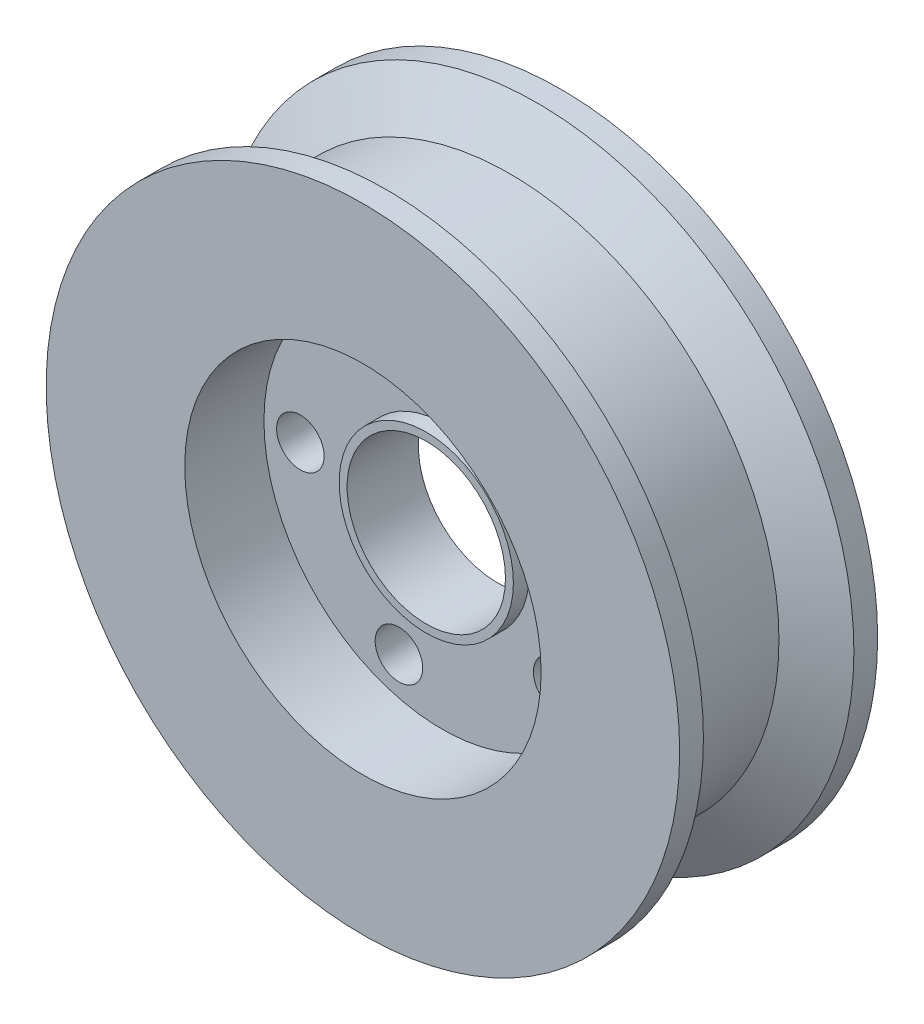
SolidWorks part; units mm, degrees
ref_plane "Front Plane" through (0, 0, 0) normal (0, 0, 1) x (1, 0, 0)
ref_plane "Top Plane" through (0, 0, 0) normal (0, 1, 0) x (1, 0, 0)
ref_plane "Right Plane" through (0, 0, 0) normal (1, 0, 0) x (0, 0, -1)
sketch "Sketch1" plane through (0, 0, 0) normal (0, 0, 1) x (1, 0, 0)
  circle A0 centre (0, 0) radius 40
  circle A1 centre (0, 0) radius 10
  dimension "D1" = 80
  dimension "D2" = 20
extrude "Boss-Extrude1" add sketch "Sketch1" along normal mid plane 25 contours A0 | A1
sketch "Sketch2" plane through (0, 0, 12.5) normal (0, 0, 1) x (1, 0, 0)
  circle A0 centre (0, 0) radius 22.5
  circle A1 centre (0, 0) radius 40 construction
  dimension "D1" = 17.5
extrude "Cut-Extrude1" cut sketch "Sketch2" against normal blind 10
mirror "Mirror1" about plane through (0, 0, 0) normal (0, 0, 1) of "Cut-Extrude1"
sketch "Sketch3" plane through (0, 0, 2.5) normal (0, 0, 1) x (1, 0, 0)
  circle A0 centre (-5.6107, 17) radius 3
  dimension "D1" = 6
  dimension "D2" = 17
extrude "Cut-Extrude2" cut sketch "Sketch3" against normal through all
pattern_circular "CirPattern1" count 5 over 360 about axis through (0, 0, 0) along (0, 0, 1) of "Cut-Extrude2"
sketch "Sketch4" plane through (0, 0, 2.5) normal (0, 0, 1) x (1, 0, 0)
  circle A0 centre (0, 0) radius 10 construction
  circle A1 centre (0, 0) radius 10
  circle A2 centre (0, 0) radius 11
  dimension "D1" = 22
extrude "Boss-Extrude2" add sketch "Sketch4" along normal blind 2 and the other way blind 7
sketch "Sketch5" plane through (0, 0, 0) normal (0, 1, 0) x (1, 0, 0)
  line L0 (0, 0) -> (0, 21.7365) construction
  line L1 (-40, -9.5) -> (-34, -6.0359)
  line L2 (-40, 12.5) -> (-40, -12.5) construction
  line L3 (-34, -6.0359) -> (-34, 6.0359)
  line L4 (-34, 6.0359) -> (-40, 9.5)
  line L5 (-40, 9.5) -> (-40, -9.5)
  dimension "D1" = 3
  dimension "D2" = 3
  dimension "D3" = 60
  dimension "D4" = 60
  dimension "D5" = 6
revolve "Cut-Revolve1" cut sketch "Sketch5" angle 360 about L0
